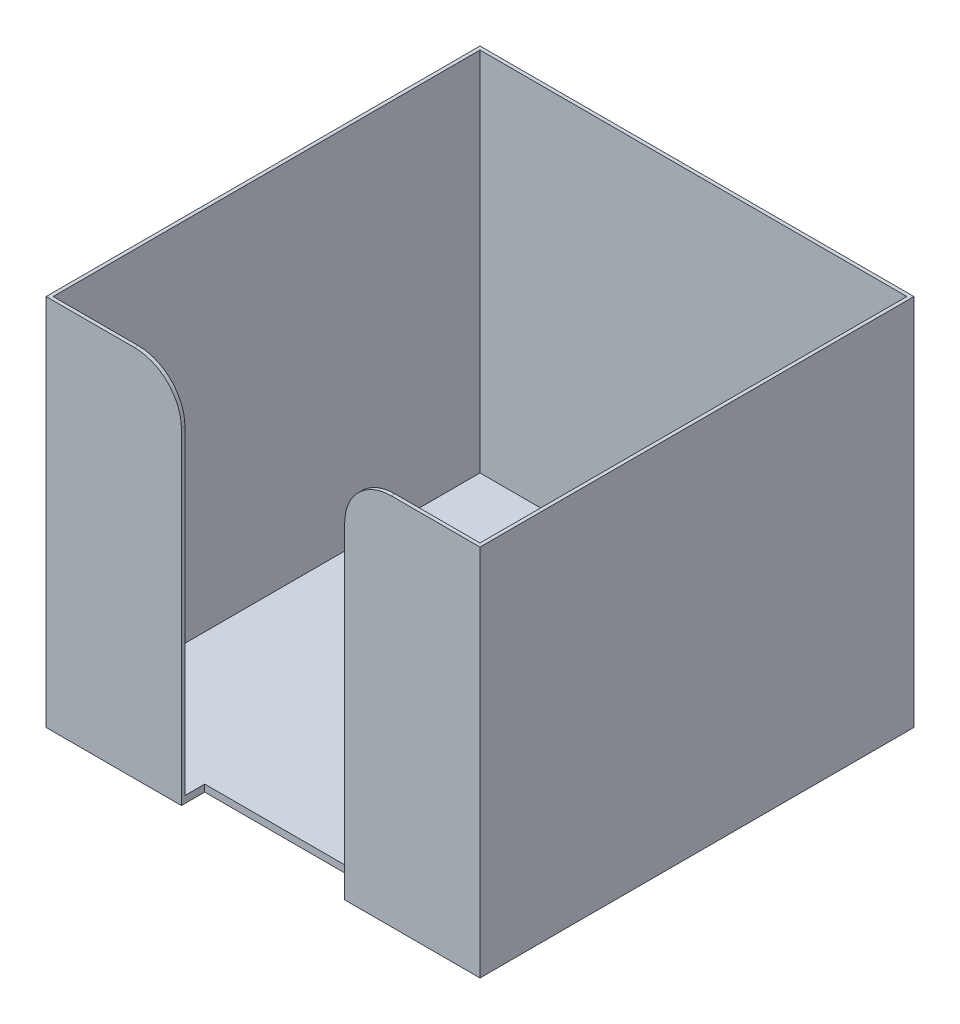
SolidWorks part; units mm, degrees
ref_plane "Front Plane" through (0, 0, 0) normal (0, 0, 1) x (1, 0, 0)
ref_plane "Top Plane" through (0, 0, 0) normal (0, 1, 0) x (1, 0, 0)
ref_plane "Right Plane" through (0, 0, 0) normal (1, 0, 0) x (0, 0, -1)
sketch "Sketch2" plane through (0, 0, 0) normal (0, 1, 0) x (1, 0, 0)
  line L1 (-46.5, -46.5) -> (46.5, -46.5)
  line L2 (-46.5, -46.5) -> (-46.5, 46.5)
  line L3 (-46.5, 46.5) -> (46.5, 46.5)
  line L4 (46.5, -46.5) -> (46.5, 46.5)
  line L5 (-46.5, -46.5) -> (46.5, 46.5) construction
  line L6 (-46.5, 46.5) -> (46.5, -46.5) construction
  point P0 (0, 0)
  dimension "D1" = 93
  dimension "D2" = 93
extrude "Boss-Extrude2" add sketch "Sketch2" along normal blind 80 contours L2 L3 L4 L1
sketch "Sketch3" plane through (0, 80, 0) normal (0, 1, 0) x (1, 0, 0)
  line L1 (45.75, -45.75) -> (-45.75, -45.75)
  line L2 (45.75, -45.75) -> (45.75, 45.75)
  line L3 (45.75, 45.75) -> (-45.75, 45.75)
  line L4 (-45.75, -45.75) -> (-45.75, 45.75)
  line L5 (45.75, -45.75) -> (-45.75, 45.75) construction
  line L6 (45.75, 45.75) -> (-45.75, -45.75) construction
  point P0 (0, 0)
  dimension "D1" = 91.5
  dimension "D2" = 91.5
extrude "Cut-Extrude1" cut sketch "Sketch3" against normal blind 78.5
sketch "Sketch6" plane through (0, 0, 46.5) normal (0, 0, 1) x (1, 0, 0)
  line L0 (-46.5, 80) -> (46.5, 80) construction
  line L1 (-17.5, 80) -> (17.5, 80)
  line L2 (-17.5, 80) -> (-17.5, 0)
  line L3 (-17.5, 0) -> (17.5, 0)
  line L4 (17.5, 80) -> (17.5, 0)
  line L5 (-46.5, 0) -> (46.5, 0) construction
  line L6 (-46.5, 80) -> (-46.5, 0) construction
  dimension "D1" = 29
  dimension "D2" = 35
extrude "Cut-Extrude2" cut sketch "Sketch6" against normal blind 5
fillet "Fillet1" radius 10 1 edges at (-17.5, 80, 46.125)
fillet "Fillet2" radius 10 1 edges at (17.5, 80, 46.125)
